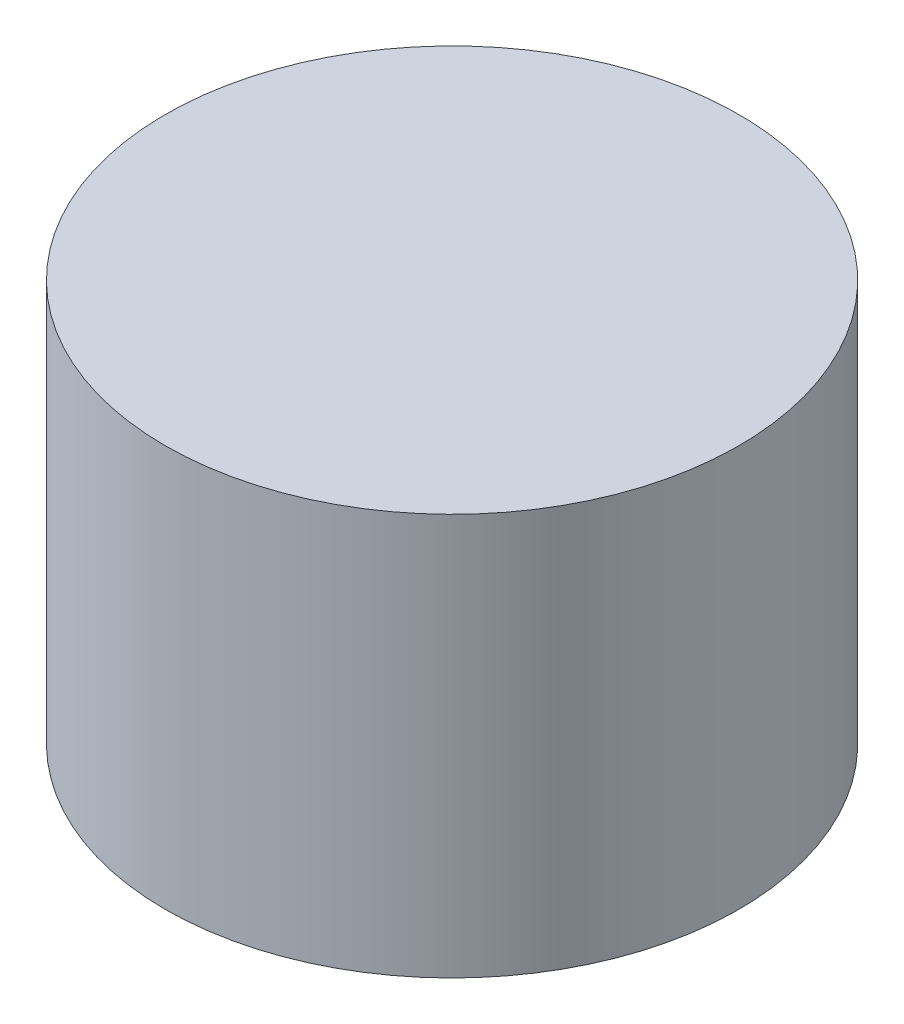
SolidWorks part; units mm, degrees
ref_plane "Front Plane" through (0, 0, 0) normal (0, 0, 1) x (1, 0, 0)
ref_plane "Top Plane" through (0, 0, 0) normal (0, 1, 0) x (1, 0, 0)
ref_plane "Right Plane" through (0, 0, 0) normal (1, 0, 0) x (0, 0, -1)
sketch "Sketch1" plane through (0, 0, 0) normal (0, 1, 0) x (1, 0, 0)
  circle A0 centre (0, 0) radius 5
  circle A1 centre (0, 0) radius 4
extrude "Boss-Extrude1" add sketch "Sketch1" along normal blind 5
sketch "Sketch2" plane through (0, 5, 0) normal (0, 1, 0) x (1, 0, 0)
  circle A0 centre (0, 0) radius 5
extrude "Boss-Extrude2" add sketch "Sketch2" along normal blind 2
